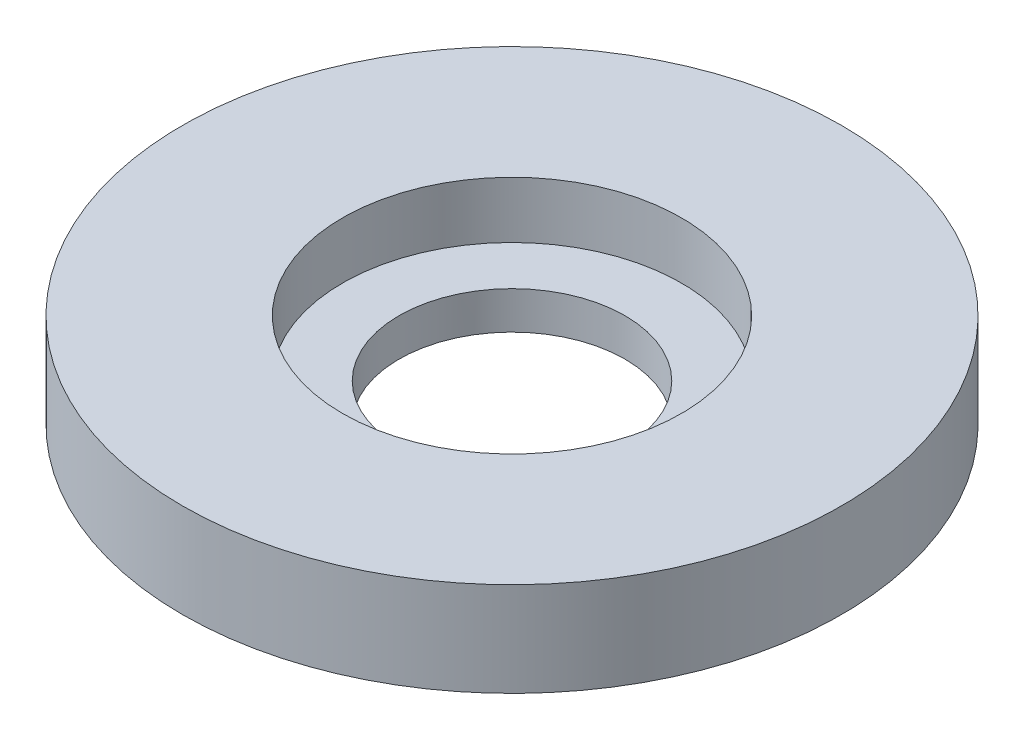
SolidWorks part; units mm, degrees
ref_plane "Front Plane" through (0, 0, 0) normal (0, 0, 1) x (1, 0, 0)
ref_plane "Top Plane" through (0, 0, 0) normal (0, 1, 0) x (1, 0, 0)
ref_plane "Right Plane" through (0, 0, 0) normal (1, 0, 0) x (0, 0, -1)
sketch "Sketch1" plane through (0, 0, 0) normal (0, 1, 0) x (1, 0, 0)
  circle A0 centre (0, 0) radius 1750
  point P3 (99.7034, 52.3188)
extrude "Boss-Extrude1" add sketch "Sketch1" along normal blind 500
sketch "Sketch2" plane through (0, 500, 0) normal (0, 1, 0) x (1, 0, 0)
  circle A0 centre (0, 0) radius 900
extrude "Cut-Extrude2" cut sketch "Sketch2" against normal blind 300
sketch "Sketch3" plane through (0, 0, 0) normal (0, -1, 0) x (1, 0, 0)
  circle A0 centre (0, 0) radius 600
extrude "Cut-Extrude3" cut sketch "Sketch3" against normal blind 300
